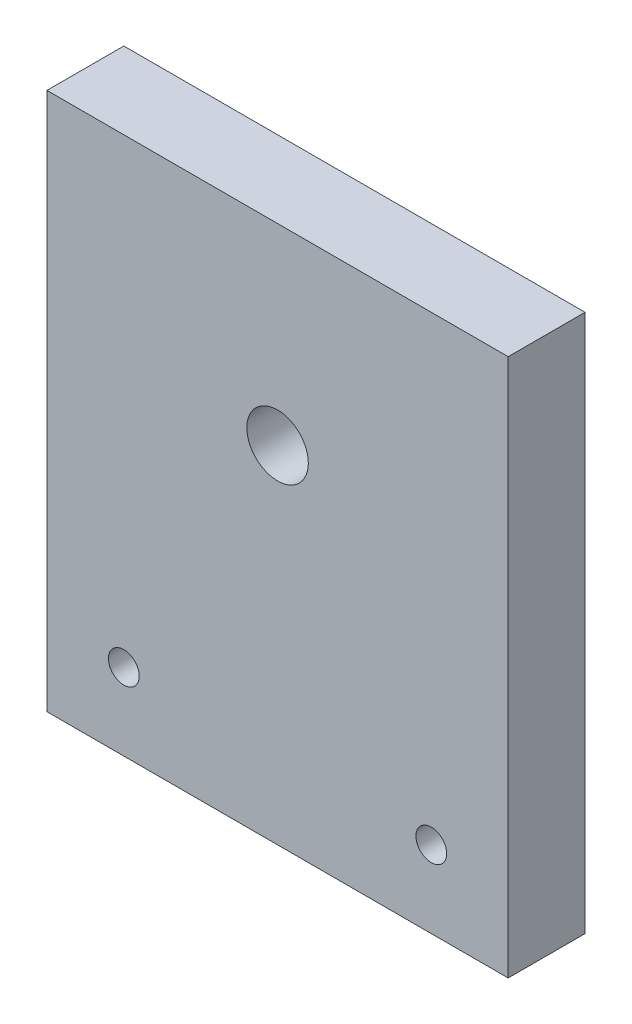
SolidWorks part; units mm, degrees
ref_plane "Front Plane" through (0, 0, 0) normal (0, 0, 1) x (1, 0, 0)
ref_plane "Top Plane" through (0, 0, 0) normal (0, 1, 0) x (1, 0, 0)
ref_plane "Right Plane" through (0, 0, 0) normal (1, 0, 0) x (0, 0, -1)
sketch "Sketch1" plane through (0, 0, 0) normal (0, 0, 1) x (1, 0, 0)
  line L0 (-30, -25) -> (30, -25) construction
  line L1 (-30, 25) -> (30, 25)
  line L2 (-30, 25) -> (-30, -45)
  line L3 (-30, -45) -> (30, -45)
  line L4 (30, 25) -> (30, -45)
  line L5 (-30, 25) -> (30, -45) construction
  line L6 (-30, -45) -> (30, 25) construction
  circle A0 centre (-20, -35) radius 2
  circle A1 centre (20, -35) radius 2
  circle A2 centre (0, 0) radius 4
  circle A3 centre (0, 0) radius 11
  point P0 (0, -10)
  point P15 (0, 0)
  dimension "D3" = 4
  dimension "D4" = 4
  dimension "D9" = 8
  dimension "D11" = 22
  dimension "D1" = 60
  dimension "D2" = 70
  dimension "D5" = 10
  dimension "D6" = 10
  dimension "D7" = 10
  dimension "D8" = 10
  dimension "D10" = 45
  dimension "D12" = 20
extrude "Boss-Extrude1" add sketch "Sketch1" along normal blind 10 contours A3 A2 | L4 L1 L2 L3 A3 A1 A0
